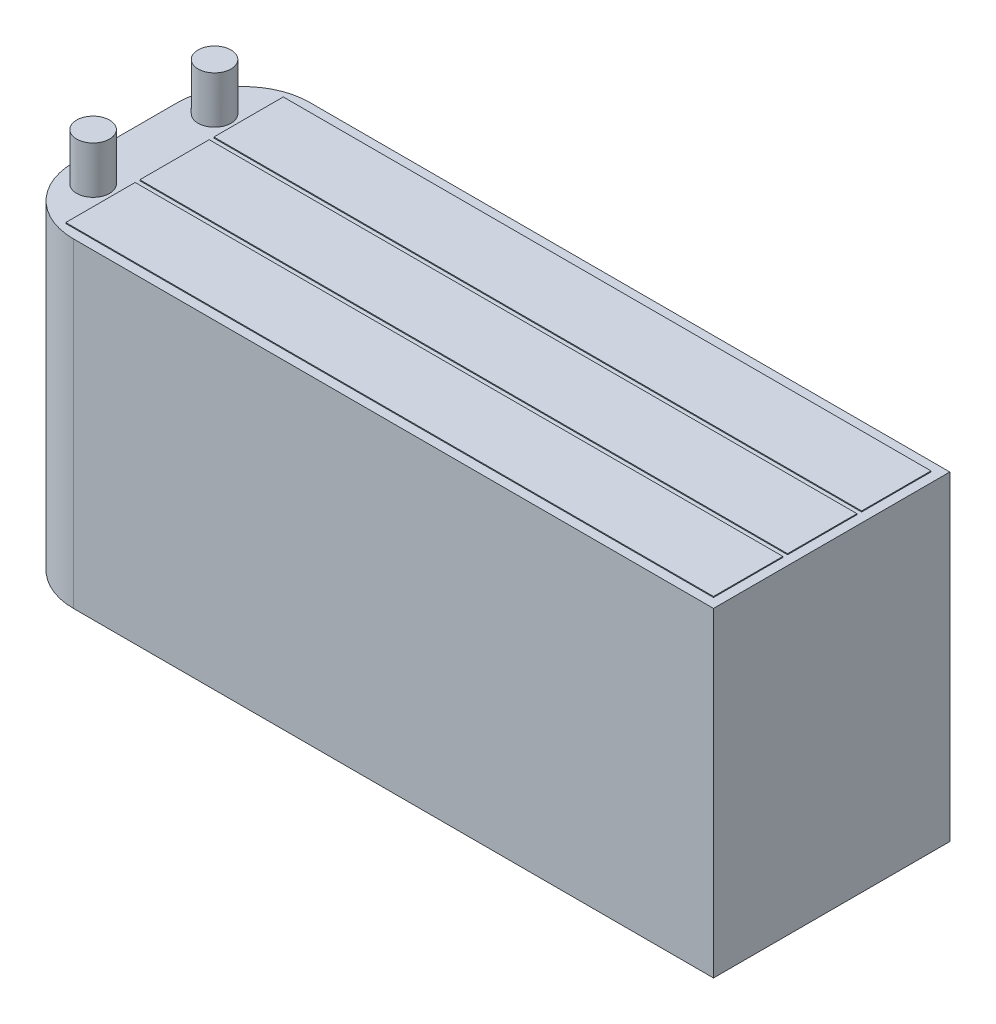
SolidWorks part; units mm, degrees
ref_plane "Front Plane" through (0, 0, 0) normal (0, 0, 1) x (1, 0, 0)
ref_plane "Top Plane" through (0, 0, 0) normal (0, 1, 0) x (1, 0, 0)
ref_plane "Right Plane" through (0, 0, 0) normal (1, 0, 0) x (0, 0, -1)
sketch "Sketch1" plane through (0, 0, 0) normal (0, 0, 1) x (1, 0, 0)
  line L1 (-37.5, -17) -> (37.5, -17)
  line L2 (-37.5, -17) -> (-37.5, 17)
  line L3 (-37.5, 17) -> (37.5, 17)
  line L4 (37.5, -17) -> (37.5, 17)
  line L5 (-37.5, -17) -> (37.5, 17) construction
  line L6 (-37.5, 17) -> (37.5, -17) construction
  point P0 (0, 0)
  dimension "D1" = 75
  dimension "D2" = 34
extrude "Boss-Extrude1" add sketch "Sketch1" along normal blind 25.1
fillet "Fillet1" radius 7 2 edges at (-37.5, 0, 0) (-37.5, 0, 25.1)
sketch "Sketch2" plane through (0, 17, 0) normal (0, 1, 0) x (1, 0, 0)
  line L0 (36.5, -20.4167) -> (37.5, -20.4167) construction
  line L1 (36.5, -1) -> (-32.3, -1)
  line L2 (36.5, -1) -> (36.5, -8.3667)
  line L3 (36.5, -8.3667) -> (-32.3, -8.3667)
  line L4 (-32.3, -1) -> (-32.3, -8.3667)
  line L5 (36.5, -8.8667) -> (-32.3, -8.8667)
  line L6 (36.5, -8.8667) -> (36.5, -16.2333)
  line L7 (36.5, -16.2333) -> (-32.3, -16.2333)
  line L8 (-32.3, -8.8667) -> (-32.3, -16.2333)
  line L9 (-32.3, -16.7333) -> (36.5, -16.7333)
  line L10 (-32.3, -16.7333) -> (-32.3, -24.1)
  line L11 (-32.3, -24.1) -> (36.5, -24.1)
  line L12 (36.5, -16.7333) -> (36.5, -24.1)
  line L13 (37.5, -25.1) -> (37.5, 0) construction
  line L14 (36.5, -12.55) -> (37.5, -12.55) construction
  line L15 (36.5, -4.6833) -> (37.5, -4.6833) construction
  line L16 (37.5, -4.6833) -> (37.5, -12.55) construction
  line L17 (37.5, -12.55) -> (37.5, -20.4167) construction
  line L18 (2.1, -8.8667) -> (2.1, -8.3667) construction
  line L19 (2.1, -16.2333) -> (2.1, -16.7333) construction
  line L20 (2.1, -1) -> (2.1, 0) construction
  line L21 (37.5, 0) -> (-30.5, 0) construction
  line L22 (2.1, -24.1) -> (2.1, -25.1) construction
  line L23 (37.5, -25.1) -> (-30.5, -25.1) construction
  dimension "D1" = 0.5
  dimension "D2" = 1
  dimension "D3" = 1
extrude "Boss-Extrude2" add sketch "Sketch2" along normal blind 0.1 separate body
mirror "Mirror1" about plane through (0, 0, 0) normal (0, 1, 0) of bodies 115 120 119 117
sketch "Sketch3" plane through (0, 17, 0) normal (0, 1, 0) x (1, 0, 0)
  line L0 (-34.5, -6.1) -> (-34.5, -19) construction
  line L1 (-37.5, -12.55) -> (-34.5, -12.55) construction
  line L2 (-37.5, -18.1) -> (-37.5, -7) construction
  circle A0 centre (-34.5, -6.1) radius 1.75
  circle A1 centre (-34.5, -19) radius 1.75
  point P8 (-34.6196, -12.55)
  dimension "D1" = 3.5
  dimension "D2" = 3
extrude "Boss-Extrude3" add sketch "Sketch3" along normal blind 5
